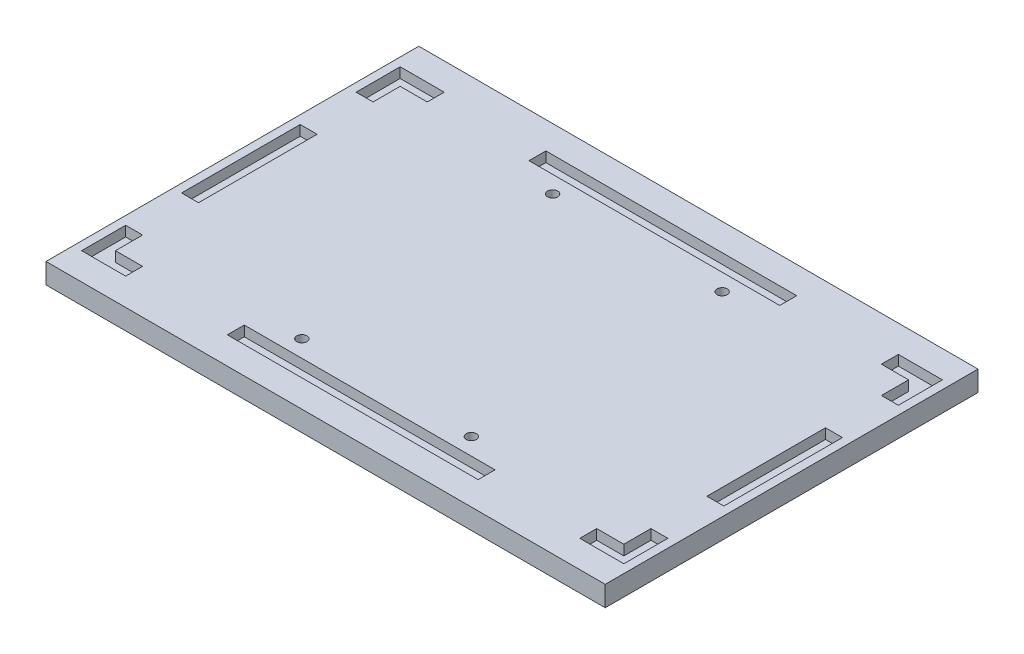
SolidWorks part; units mm, degrees
ref_plane "Front Plane" through (0, 0, 0) normal (0, 0, 1) x (1, 0, 0)
ref_plane "Top Plane" through (0, 0, 0) normal (0, 1, 0) x (1, 0, 0)
ref_plane "Right Plane" through (0, 0, 0) normal (1, 0, 0) x (0, 0, -1)
sketch "Sketch1" plane through (0, 0, 0) normal (0, 1, 0) x (1, 0, 0)
  line L1 (-95.1587, 56.746) -> (69.8413, 56.746)
  line L2 (-95.1587, 56.746) -> (-95.1587, -53.254)
  line L3 (-95.1587, -53.254) -> (69.8413, -53.254)
  line L4 (69.8413, 56.746) -> (69.8413, -53.254)
  dimension "D1" = 110
  dimension "D2" = 165
extrude "Boss-Extrude1" add sketch "Sketch1" along normal blind 6 contours L1 L4 L3 L2
sketch "Sketch2" plane through (0, 6, 0) normal (0, 1, 0) x (1, 0, 0)
  line L0 (-70.1587, 54.246) -> (-37.6587, 54.246) construction
  line L12 (-95.1587, 56.746) -> (69.8413, 56.746) construction
  line L13 (-92.6587, 48.746) -> (67.3413, 48.746) construction
  line L32 (-92.6587, 48.746) -> (-92.6587, -45.254) construction
  line L33 (-92.6587, -45.254) -> (67.3413, -45.254) construction
  line L34 (67.3413, 48.746) -> (67.3413, -45.254) construction
  line L36 (-95.1587, -53.254) -> (69.8413, -53.254) construction
  line L37 (-95.1587, 56.746) -> (-95.1587, -53.254) construction
  line L38 (69.8413, 56.746) -> (69.8413, -53.254) construction
  line L39 (-92.6587, 48.746) -> (-92.6587, 35.746)
  line L40 (-92.6587, 35.746) -> (-87.6587, 35.746)
  line L41 (-87.6587, 35.746) -> (-87.6587, 43.746)
  line L42 (-87.6587, 43.746) -> (-79.6587, 43.746)
  line L43 (-79.6587, 43.746) -> (-79.6587, 48.746)
  line L44 (-79.6587, 48.746) -> (-92.6587, 48.746)
  line L45 (-106.2643, 1.746) -> (82.4028, 1.746) construction
  line L46 (-12.6587, 67.4112) -> (-12.6587, -62.8099) construction
  line L47 (-79.6587, -40.254) -> (-79.6587, -45.254)
  line L48 (-87.6587, -40.254) -> (-79.6587, -40.254)
  line L49 (-87.6587, -32.254) -> (-87.6587, -40.254)
  line L50 (-92.6587, -32.254) -> (-87.6587, -32.254)
  line L51 (-92.6587, -45.254) -> (-92.6587, -32.254)
  line L52 (-79.6587, -45.254) -> (-92.6587, -45.254)
  line L53 (54.3413, 43.746) -> (54.3413, 48.746)
  line L54 (62.3413, 43.746) -> (54.3413, 43.746)
  line L55 (62.3413, 35.746) -> (62.3413, 43.746)
  line L56 (67.3413, 35.746) -> (62.3413, 35.746)
  line L57 (67.3413, 48.746) -> (67.3413, 35.746)
  line L58 (54.3413, 48.746) -> (67.3413, 48.746)
  line L59 (62.3413, -40.254) -> (54.3413, -40.254)
  line L60 (62.3413, -32.254) -> (62.3413, -40.254)
  line L61 (67.3413, -32.254) -> (62.3413, -32.254)
  line L62 (67.3413, -45.254) -> (67.3413, -32.254)
  line L63 (54.3413, -45.254) -> (67.3413, -45.254)
  line L64 (54.3413, -40.254) -> (54.3413, -45.254)
  line L65 (67.3413, -15.754) -> (62.3413, -15.754)
  line L66 (-92.6587, 19.246) -> (-87.6587, 19.246)
  line L67 (-92.6587, 19.246) -> (-92.6587, -15.754)
  line L68 (-92.6587, -15.754) -> (-87.6587, -15.754)
  line L69 (-87.6587, 19.246) -> (-87.6587, -15.754)
  line L70 (62.3413, 19.246) -> (62.3413, -15.754)
  line L71 (67.3413, 19.246) -> (62.3413, 19.246)
  line L72 (67.3413, 19.246) -> (67.3413, -15.754)
  line L73 (-49.6587, -40.254) -> (24.3413, -40.254)
  line L74 (-49.6587, 48.746) -> (24.3413, 48.746)
  line L75 (-49.6587, 48.746) -> (-49.6587, 43.746)
  line L76 (-49.6587, 43.746) -> (24.3413, 43.746)
  line L77 (24.3413, 48.746) -> (24.3413, 43.746)
  line L78 (24.3413, -45.254) -> (24.3413, -40.254)
  line L79 (-49.6587, -45.254) -> (24.3413, -45.254)
  line L80 (-49.6587, -45.254) -> (-49.6587, -40.254)
  line L81 (-95.1587, 52.0662) -> (-70.1587, 52.0662) construction
  line L82 (-70.1587, 52.0662) -> (-70.1587, 45.4053) construction
  dimension "D1" = 8
  dimension "D2" = 8
  dimension "D3" = 2.5
  dimension "D4" = 2.5
  dimension "D5" = 5
  dimension "D6" = 5
  dimension "D7" = 8
  dimension "D8" = 8
  dimension "D9" = 35
  dimension "D10" = 16.5
  dimension "D11" = 30
  dimension "D12" = 30
  dimension "D13" = 25
  dimension "D17" = 32.5
  dimension "D19" = 2.5
extrude "Cut-Extrude1" cut sketch "Sketch2" against normal blind 3
sketch "Sketch4" plane through (0, 6, 0) normal (0, 1, 0) x (1, 0, 0)
  line L1 (-12.6587, 56.746) -> (-12.6587, -53.254) construction
  line L2 (-49.6587, 43.746) -> (24.3413, 43.746) construction
  line L3 (-49.6587, 43.746) -> (24.3413, 43.746) construction
  line L4 (-95.1587, 56.746) -> (69.8413, 56.746) construction
  line L5 (-95.1587, 1.746) -> (69.8413, 1.746) construction
  line L6 (-95.1587, 56.746) -> (-95.1587, -53.254) construction
  line L7 (69.8413, 56.746) -> (69.8413, -53.254) construction
  line L8 (-95.1587, -53.254) -> (69.8413, -53.254) construction
  circle A0 centre (-37.6587, 38.746) radius 1.5
  circle A1 centre (12.3413, 38.746) radius 1.5
  circle A3 centre (12.3413, -35.254) radius 1.5
  circle A5 centre (-37.6587, -35.254) radius 1.5
  dimension "D3" = 5
  dimension "D1" = 5
extrude "Cut-Extrude2" cut sketch "Sketch4" against normal through all
